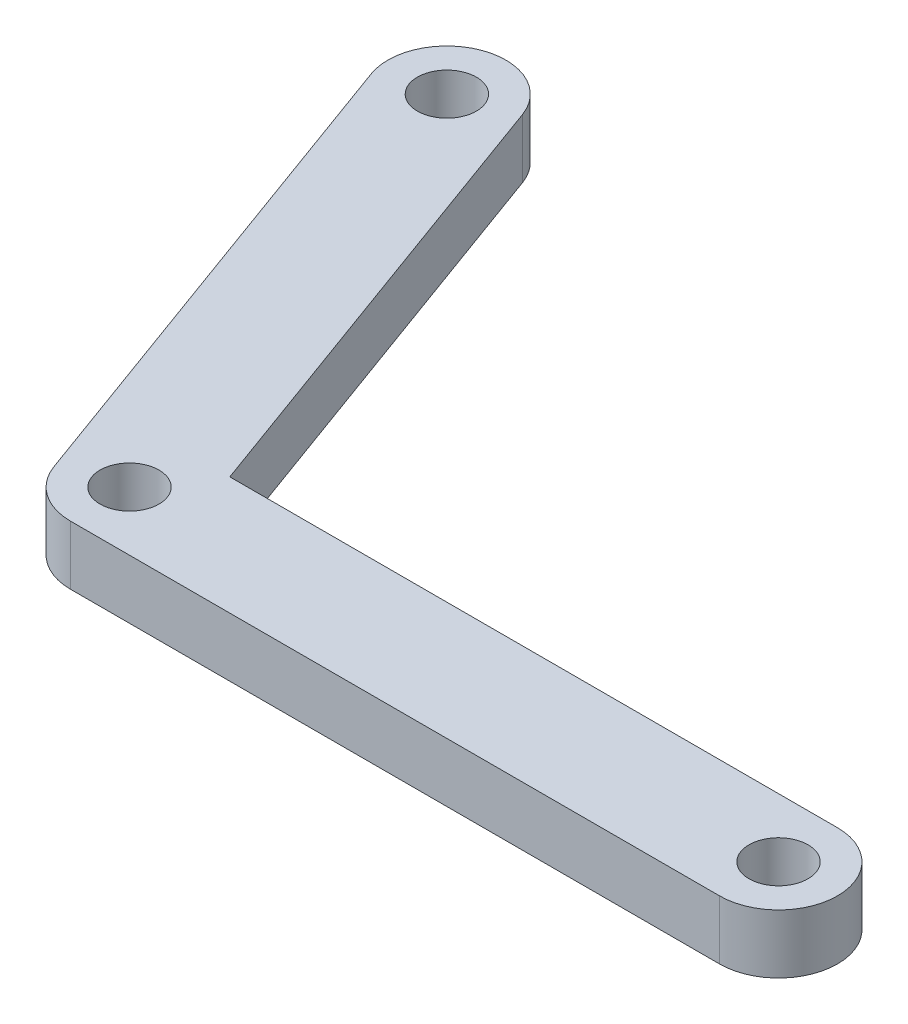
SolidWorks part; units mm, degrees
ref_plane "Plan de face" through (0, 0, 0) normal (0, 0, 1) x (1, 0, 0)
ref_plane "Plan de dessus" through (0, 0, 0) normal (0, 1, 0) x (1, 0, 0)
ref_plane "Plan de droite" through (0, 0, 0) normal (1, 0, 0) x (0, 0, -1)
sketch "Esquisse2" plane through (0, 0, 0) normal (0, 1, 0) x (1, 0, 0)
  line L0 (0, 0) -> (55, 0) construction
  line L1 (0, 5) -> (55, 5)
  line L2 (0, -5) -> (55, -5)
  line L3 (0, 0) -> (-15.3909, 42.2862) construction
  line L4 (-4.6985, -1.7101) -> (-20.0894, 40.5761)
  line L5 (4.6985, 1.7101) -> (-10.6924, 43.9963)
  arc A0 (0, 5) -> (0, -5) centre (0, 0) ccw
  arc A1 (55, -5) -> (55, 5) centre (55, 0) ccw
  arc A2 (-4.6985, -1.7101) -> (4.6985, 1.7101) centre (0, 0) ccw
  arc A3 (-10.6924, 43.9963) -> (-20.0894, 40.5761) centre (-15.3909, 42.2862) ccw
  point P3 (27.5, 0)
  point P10 (-7.6955, 21.1431)
  dimension "D3" = 5
  dimension "D4" = 5
  dimension "D1" = 55
  dimension "D2" = 45
  dimension "D5" = 110
extrude "Boss.-Extru.1" add sketch "Esquisse2" along normal blind 5 contours L5 A3 L4 A0 L1 | A2 L2 A1 L1 L5 | A0 A2 L5 L1
sketch "Esquisse3" plane through (0, 5, 0) normal (0, 1, 0) x (1, 0, 0)
  circle A0 centre (-15.3909, 42.2862) radius 2.5
  circle A1 centre (55, 0) radius 2.5
  dimension "D1" = 5
  dimension "D2" = 5
extrude "Enlèv. mat.-Extru.1" cut sketch "Esquisse3" against normal blind 5
sketch "Esquisse4" plane through (0, 5, 0) normal (0, 1, 0) x (1, 0, 0)
  circle A0 centre (0, 0) radius 2.5
  dimension "D1" = 5
extrude "Enlèv. mat.-Extru.2" cut sketch "Esquisse4" against normal blind 5
